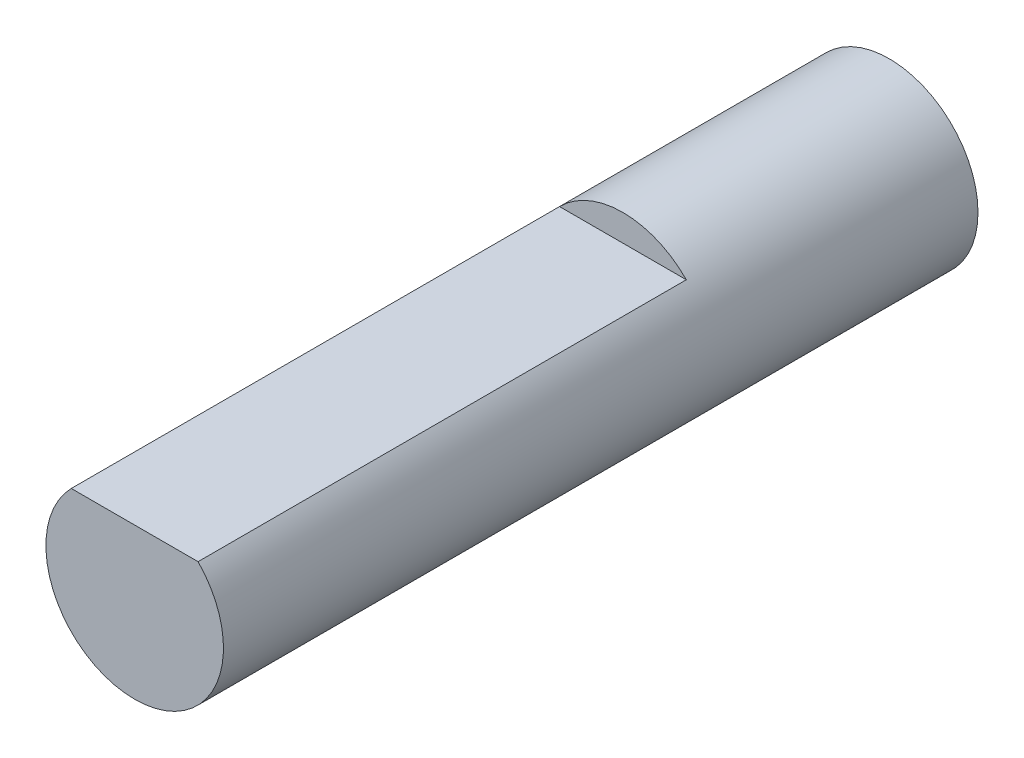
SolidWorks part; units mm, degrees
ref_plane "Alzado" through (0, 0, 0) normal (0, 0, 1) x (1, 0, 0)
ref_plane "Planta" through (0, 0, 0) normal (0, 1, 0) x (1, 0, 0)
ref_plane "Vista lateral" through (0, 0, 0) normal (1, 0, 0) x (0, 0, -1)
sketch "Croquis1" plane through (0, 0, 0) normal (0, 0, 1) x (1, 0, 0)
  circle A0 centre (0, 0) radius 2
  dimension "D1" = 4
extrude "Saliente-Extruir1" add sketch "Croquis1" along normal blind 17
sketch "Croquis2" plane through (0, 0, 17) normal (0, 0, 1) x (1, 0, 0)
  line L1 (-1.4283, 1.4) -> (1.4283, 1.4)
  circle A0 centre (0, 0) radius 2 construction
  arc A1 (1.4283, 1.4) -> (-1.4283, 1.4) centre (0, 0) ccw
  point P8 (0, 1.4)
extrude "Cortar-Extruir1" cut sketch "Croquis2" against normal blind 11
